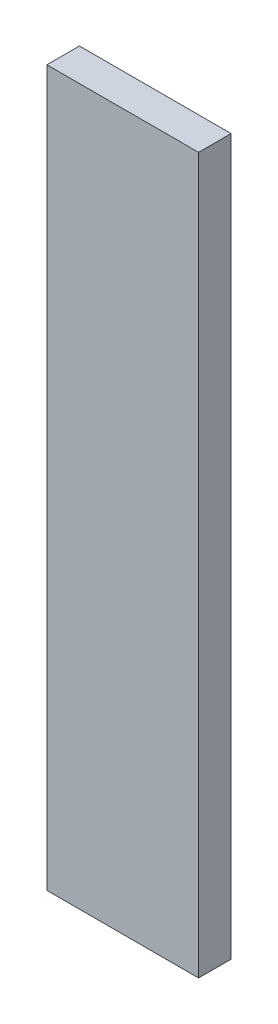
SolidWorks part; units mm, degrees
ref_plane "Front Plane" through (0, 0, 0) normal (0, 0, 1) x (1, 0, 0)
ref_plane "Top Plane" through (0, 0, 0) normal (0, 1, 0) x (1, 0, 0)
ref_plane "Right Plane" through (0, 0, 0) normal (1, 0, 0) x (0, 0, -1)
sketch "Sketch1" plane through (0, 0, 0) normal (0, 1, 0) x (1, 0, 0)
  line L1 (0, 0) -> (88.9, 0)
  line L2 (0, 0) -> (0, 19.05)
  line L3 (0, 19.05) -> (88.9, 19.05)
  line L4 (88.9, 0) -> (88.9, 19.05)
  dimension "D1" = 19.05
  dimension "D2" = 88.9
extrude "Boss-Extrude1" add sketch "Sketch1" along normal blind 419.1
